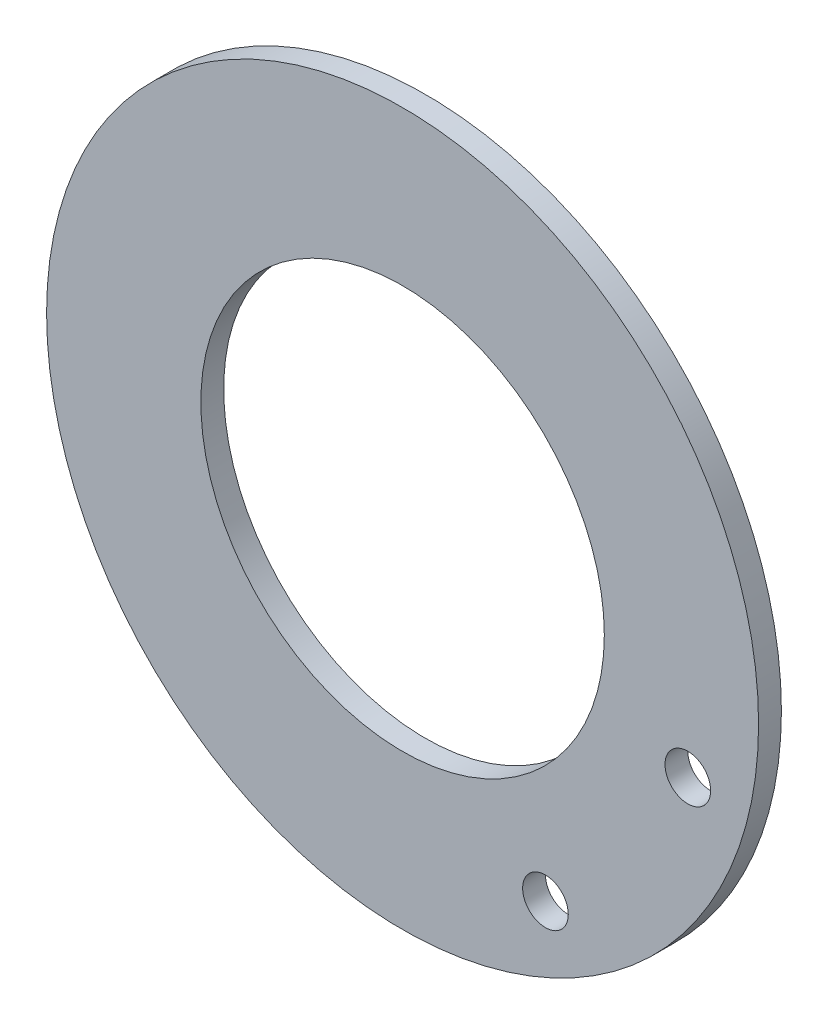
SolidWorks part; units mm, degrees
ref_plane "Front Plane" through (0, 0, 0) normal (0, 0, 1) x (1, 0, 0)
ref_plane "Top Plane" through (0, 0, 0) normal (0, 1, 0) x (1, 0, 0)
ref_plane "Right Plane" through (0, 0, 0) normal (1, 0, 0) x (0, 0, -1)
sketch "Sketch1" plane through (0, 0, 0) normal (0, 0, 1) x (1, 0, 0)
  circle A0 centre (0, 0) radius 49.53
  circle A1 centre (0, 0) radius 28.067
  dimension "D1" = 99.06
  dimension "D2" = 56.134
extrude "Boss-Extrude1" add sketch "Sketch1" along normal blind 3.175
extrude "Cut-Extrude1" cut sketch "Sketch2" against normal blind 22.86
sketch "Sketch2" plane through (182.0111, -492.1061, 3.175) normal (0, 0, 1) x (0.6238, 0.7816, 0)
  circle A0 centre (255.2166, 411.128) radius 3.175
  circle A1 centre (286.9666, 411.128) radius 3.175
